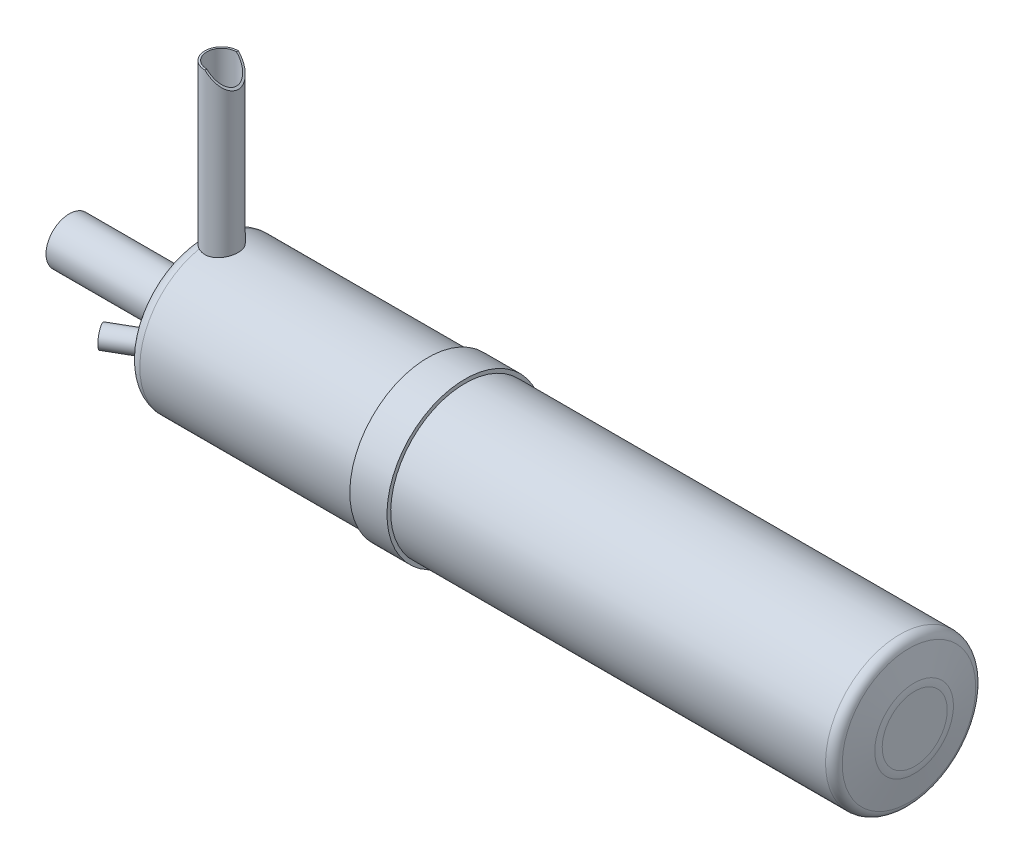
SolidWorks part; units mm, degrees
ref_plane "Front Plane" through (0, 0, 0) normal (0, 0, 1) x (1, 0, 0)
ref_plane "Top Plane" through (0, 0, 0) normal (0, 1, 0) x (1, 0, 0)
ref_plane "Right Plane" through (0, 0, 0) normal (1, 0, 0) x (0, 0, -1)
sketch "Sketch1" plane through (0, 0, 0) normal (0, 0, 1) x (1, 0, 0)
  line L0 (0, 0) -> (453, 0) construction
  line L1 (0, 12.5) -> (70, 12.5)
  line L2 (70, 12.5) -> (70, 16.8646)
  line L3 (70.0403, 18.1341) -> (71.0141, 33.4443)
  line L4 (78, 40) -> (193, 40)
  line L5 (193, 40) -> (193, 42)
  line L6 (193, 42) -> (213, 42)
  line L7 (213, 42) -> (213, 40)
  line L8 (213, 40) -> (447, 40)
  line L9 (451.9156, 35.915) -> (454.6622, 21.1602)
  line L10 (455, 17.5) -> (455, 0)
  line L11 (0, 12.5) -> (0, 10.5)
  line L12 (0, 10.5) -> (72, 10.5)
  line L13 (72, 10.5) -> (72, 16.8646)
  line L14 (455, 0) -> (453, 0)
  line L15 (453, 0) -> (453, 17.5)
  line L16 (72.0363, 18.0072) -> (73.0101, 33.3174)
  line L17 (78, 38) -> (447, 38)
  line L18 (452.696, 20.7942) -> (449.9493, 35.549)
  arc A0 (71.0141, 33.4443) -> (78, 40) centre (78, 33) cw
  arc A1 (447, 40) -> (451.9156, 35.915) centre (447, 35) cw
  arc A2 (70, 16.8646) -> (70.0403, 18.1341) centre (90, 16.8646) cw
  arc A3 (454.6622, 21.1602) -> (455, 17.5) centre (435, 17.5) cw
  arc A4 (72, 16.8646) -> (72.0363, 18.0072) centre (90, 16.8646) cw
  arc A5 (73.0101, 33.3174) -> (78, 38) centre (78, 33) cw
  arc A6 (453, 17.5) -> (452.696, 20.7942) centre (435, 17.5) ccw
  arc A7 (449.9493, 35.549) -> (447, 38) centre (447, 35) ccw
  point P23 (70, 17.5)
  dimension "D3" = 7
  dimension "D7" = 20
  dimension "D9" = 5
  dimension "D10" = 20
  dimension "D1" = 25
  dimension "D2" = 80
  dimension "D4" = 21
  dimension "D5" = 70
  dimension "D6" = 35
  dimension "D8" = 8
  dimension "D11" = 35
  dimension "D12" = 8
  dimension "D13" = 2
  dimension "D14" = 115
  dimension "D15" = 20
  dimension "D16" = 2
  dimension "D17" = 385
  dimension "D18" = 2
revolve "Revolve1" add sketch "Sketch1" angle 360 about L0
sketch "Sketch2" plane through (0, 0, 0) normal (0, 0, 1) x (1, 0, 0)
  line L0 (82.0141, 37) -> (82.0141, 125) construction
  line L1 (73.0141, 125) -> (73.0141, 37)
  line L2 (73.0141, 37) -> (74.0141, 37)
  line L3 (74.0141, 37) -> (74.0141, 125)
  line L4 (74.0141, 125) -> (73.0141, 125)
  line L6 (71.0141, -33.4443) -> (71.0141, 33.4443) construction
  line L7 (193, 40) -> (78, 40) construction
  line L8 (82.0141, 125) -> (74.0141, 125) construction
  line L9 (74.0141, 37) -> (82.0141, 37) construction
  dimension "D1" = 1
  dimension "D2" = 18
  dimension "D3" = 2
  dimension "D4" = 3
  dimension "D5" = 85
revolve "Revolve2" add sketch "Sketch2" angle 360 about L0
sketch "Sketch3" plane through (0, 0, 0) normal (0, 0, 1) x (1, 0, 0)
  line L0 (82.0141, 125) -> (91.0141, 125)
  line L1 (91.0141, 125) -> (73.0141, 125) construction
  line L2 (91.0141, 125) -> (91.0141, 116)
  line L3 (91.0141, 40) -> (91.0141, 125) construction
  line L4 (91.0141, 116) -> (82.0141, 125)
extrude "Cut-Extrude1" cut sketch "Sketch3" against normal mid plane 20
sketch "Sketch4" plane through (0, 0, 0) normal (0, 1, 0) x (1, 0, 0)
  line L0 (53.2067, -35.7892) -> (70.5272, -25.7892) construction
  line L1 (70.0403, -18.1341) -> (71.0141, -33.4443) construction
  line L2 (0, -12.5) -> (70, -12.5) construction
  line L3 (74.5093, -28.6863) -> (55.4567, -39.6863)
  line L4 (55.4567, -39.6863) -> (55.9567, -40.5524)
  line L5 (55.9567, -40.5524) -> (75.0093, -29.5524)
  line L6 (75.0093, -29.5524) -> (74.5093, -28.6863)
  line L7 (53.2067, -35.7892) -> (55.4567, -39.6863) construction
  dimension "D1" = 30
  dimension "D2" = 1
  dimension "D3" = 11
  dimension "D4" = 20
  dimension "D5" = 22
revolve "Revolve3" add sketch "Sketch4" angle 360 about L0
